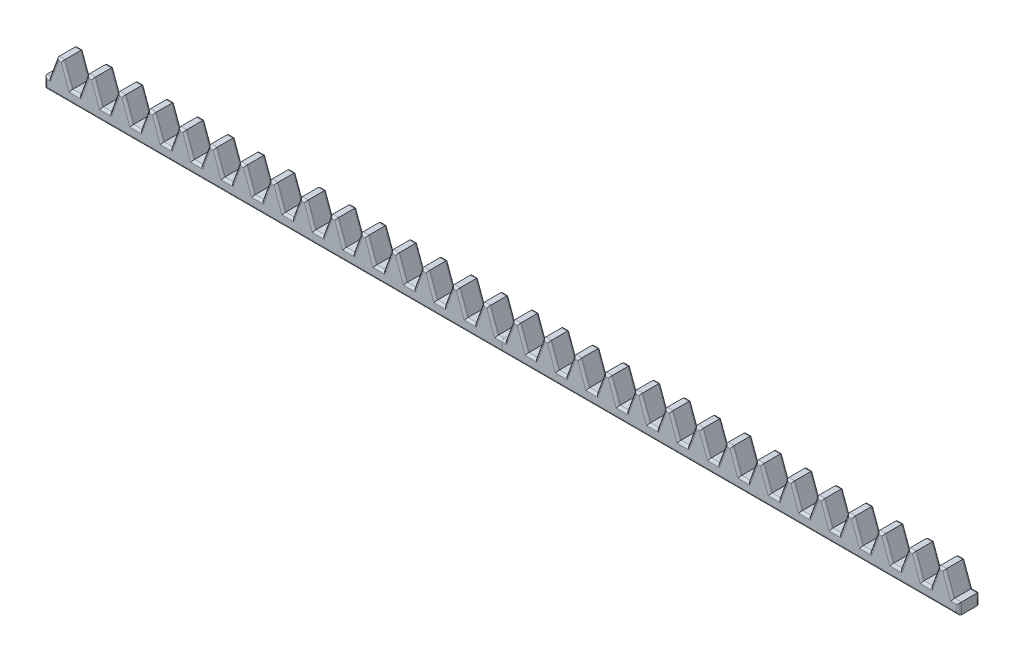
SolidWorks part; units mm, degrees
extrude "Blank" add sketch "BlankSke" against normal blind 8.89
sketch "BlankSke" plane through (0, 0, 0) normal (0, 0, 1) x (1, 0, 0)
  line L1 (0, 0) -> (400.0002, 0)
  line L2 (0, 0) -> (0, 14.3933)
  line L3 (0, 14.3933) -> (400.0002, 14.3933)
  line L4 (400.0002, 0) -> (400.0002, 14.3933)
  dimension "Length" = 400.0002
  dimension "Blank_height" = 14.3933
ref_plane "Plane1" through (0, 0, 0) normal (0, 0, 1) x (1, 0, 0)
ref_plane "Plane2" through (0, 0, 0) normal (0, 1, 0) x (1, 0, 0)
ref_plane "Plane3" through (0, 0, 0) normal (1, 0, 0) x (0, 0, -1)
sketch "HoldingSke" plane through (0, 0, 0) normal (0, 1, 0) x (1, 0, 0)
  line L0 (0, 0) -> (116.7452, -97.9608)
  line L1 (-15, 0) -> (100, 0) construction
  line L2 (0, 0) -> (-2.1039, 2.3779)
  line L3 (0, 0) -> (-11.863, 4.5341)
  line L4 (0, 0) -> (6.5177, 5.6657)
  line L5 (0, 0) -> (-23.7986, -8.8762)
  line L6 (0, 0) -> (-10.5278, -7.1032)
  line L9 (-71.009, 38.7566) -> (417.6302, 216.6067)
  line L10 (-76.2, 71.12) -> (-66.04, 71.12)
  line L11 (0, 0) -> (-8.89, 0)
  line L12 (-76.2, 101.6) -> (-76.0298, 101.6)
  line L13 (24.9733, 27.94) -> (52.9518, 28.4284)
  line L14 (24.9733, 27.94) -> (24.9746, 27.94)
  line L15 (24.9733, 27.94) -> (100.4006, 29.5858)
  circle A0 centre (0, 0) radius 19.05
  circle A1 centre (0, 0) radius 5.08
  circle A2 centre (0, 0) radius 12.7
  dimension "MPH" = 10.16
  dimension "Diameter" = 38.1
  dimension "Num_teeth" = 41
  dimension "Pitch" = 152.4
  dimension "Show_teeth" = 400
  dimension "Thickness" = 12.7
  dimension "Ap" = 20
  dimension "Pitch_height" = 10.16
  dimension "Width" = 8.89
  dimension "Backlash" = 0.1702
  dimension "Addendum_fac" = 1
  dimension "Dedendum_fac" = 1.25
  dimension "Clearance_fac" = 0.25
  dimension "Dedendum_add" = 0.0013
  dimension "Length" = 519.999
sketch "TooCutSkeIll" plane through (0, 0, 0) normal (0, 0, 1) x (1, 0, 0)
  line L0 (-5.3356, 14.2819) -> (-2.1631, 5.5655)
  line L1 (-1.1674, 4.8683) -> (1.1674, 4.8683)
  line L2 (2.1631, 5.5655) -> (5.3356, 14.2819)
  line L3 (400.0002, 14.3933) -> (0, 14.3933) construction
  line L4 (0, 0) -> (0, 64.897) construction
  line L5 (-13.208, 10.16) -> (12.954, 10.16) construction
  line L6 (0, 0) -> (400.0002, 0) construction
  line L7 (3.8354, 10.16) -> (3.8354, 48.7463) construction
  line L8 (-3.8354, 10.16) -> (-3.8354, 48.7463) construction
  line L9 (5.4948, 14.3933) -> (5.4948, 14.4187)
  line L10 (-5.4948, 14.3933) -> (-5.4948, 14.4187)
  line L11 (-5.4948, 14.4187) -> (5.4948, 14.4187)
  arc A0 (1.1674, 4.8683) -> (2.1631, 5.5655) centre (1.1674, 5.9279) ccw
  arc A1 (-2.1631, 5.5655) -> (-1.1674, 4.8683) centre (-1.1674, 5.9279) ccw
  arc A2 (5.4948, 14.3933) -> (5.3356, 14.2819) centre (5.4948, 14.224) ccw
  arc A3 (-5.3356, 14.2819) -> (-5.4948, 14.3933) centre (-5.4948, 14.224) ccw
  dimension "Pitch_height" = 10.16
  dimension "Addendum_plus" = 4.2587
  dimension "Pressure_angle" = 20
  dimension "Gap_width" = 7.6708
  dimension "Dedendum" = 5.2917
extrude "ToothCutIll" [suppressed] cut sketch "TooCutSkeIll" against normal through all
sketch "TooCutSkeSim" plane through (0, 0, 0) normal (0, 0, 1) x (1, 0, 0)
  line L0 (1.9094, 4.8683) -> (-1.9094, 4.8683)
  line L1 (5.3854, 14.4187) -> (1.9094, 4.8683)
  line L2 (0, 17.4625) -> (0, 53.467) construction
  line L3 (5.3854, 14.4187) -> (-5.3854, 14.4187)
  line L6 (-5.3854, 14.4187) -> (-1.9094, 4.8683)
  line L9 (-3.8354, 10.16) -> (3.8354, 10.16) construction
  line L10 (0, 0) -> (400.0002, 0) construction
  line L11 (3.8354, 10.16) -> (3.8354, 53.467) construction
  line L12 (-3.8354, 10.16) -> (-3.8354, 53.467) construction
  dimension "Pitch_height" = 10.16
  dimension "Addendum_plus" = 4.2587
  dimension "Pressure_angle" = 20
  dimension "Gap_width" = 7.6708
  dimension "Dedendum" = 5.2917
extrude "ToothCutSim" cut sketch "TooCutSkeSim" against normal through all
pattern_linear "TeethCuts" count 31 spacing 13.2994 along (1, 0, 0) of "ToothCutIll", "ToothCutSim"
ref_plane "Plane4" through (200.0001, 0, 0) normal (-1, 0, 0) x (0, 0, 1)
fillet "Fillet1" radius 1 74 edges at (395.3395, 9.6308, -8.89) (385.6829, 4.8683, -8.89) (345.7846, 4.8683, -8.89) (332.4852, 4.8683, -8.89) (325.8355, 14.3933, -8.89) (319.1858, 4.8683, -8.89) (305.8864, 4.8683, -8.89) (302.2436, 9.6308, -8.89) (299.2367, 14.3933, -8.89) (296.2298, 9.6308, -8.89) (292.587, 4.8683, -8.89) (265.9882, 4.8683, -8.89) (226.09, 4.8683, -8.89) (219.4402, 14.3933, -8.89) (209.1478, 9.6308, -8.89) (203.1339, 9.6308, -8.89) (200.0001, 0, -8.89) (203.1339, 9.6308, 0) (222.4472, 9.6308, 0) (232.7397, 14.3933, 0) (235.7466, 9.6308, 0) (252.6888, 4.8683, 0) (265.9882, 4.8683, 0) (269.631, 9.6308, 0) (272.6379, 14.3933, 0) (275.6448, 9.6308, 0) (285.9373, 14.3933, 0) (296.2298, 9.6308, 0) (302.2436, 9.6308, 0) (325.8355, 14.3933, 0) (345.7846, 4.8683, 0) (368.7407, 9.6308, 0) (382.0401, 9.6308, 0) (395.3395, 9.6308, 0) (200.0001, 0, 0) (195.8483, 9.6308, -8.89) (172.8923, 4.8683, -8.89) (169.2495, 9.6308, -8.89) (166.2426, 14.3933, -8.89) (163.2357, 9.6308, -8.89) (159.5929, 4.8683, -8.89) (142.6507, 9.6308, -8.89) (113.045, 14.3933, -8.89) (86.4462, 14.3933, -8.89) (66.497, 4.8683, -8.89) (56.8404, 9.6308, -8.89) (53.1976, 4.8683, -8.89) (49.5548, 9.6308, -8.89) (39.8982, 4.8683, -8.89) (33.2485, 14.3933, -8.89) (30.2416, 9.6308, -8.89) (16.9422, 9.6308, -8.89) (0.9547, 4.8683, -8.89) (0, 2.4342, 0) (13.2994, 4.8683, 0) (16.9422, 9.6308, 0) (19.9491, 14.3933, 0) (43.541, 9.6308, 0) (49.5548, 9.6308, 0) (70.1398, 9.6308, 0) (73.1467, 14.3933, 0) (96.7387, 9.6308, 0) (102.7525, 9.6308, 0) (113.045, 14.3933, 0) (119.6947, 4.8683, 0) (136.6369, 9.6308, 0) (139.6438, 14.3933, 0) (149.9363, 9.6308, 0) (152.9432, 14.3933, 0) (166.2426, 14.3933, 0) (176.5351, 9.6308, 0) (189.8345, 9.6308, 0) (192.8414, 14.3933, 0) (195.8483, 9.6308, 0)
split "Split1" trim tools "Plane4" bodies to split 102 resulting bodies 103 104
equation "' \"Pitch@HoldingSke\" = 4"
equation "' \"Num_teeth@HoldingSke\" = 12"
equation "' \"Ap@HoldingSke\" =  20"
equation "' \"Ap@HoldingSke\" = 20"
equation "' \"Width@HoldingSke\" = 0.25"
equation "' \"Show_teeth@HoldingSke\" = 500"
equation "' \"Backlash@HoldingSke\" = 0.009"
equation "' \"Addendum_fac@HoldingSke\" = 1.0"
equation "' \"Dedendum_fac@HoldingSke\" = 1.25"
equation "' \"Dedendum_add@HoldingSke\" = 0.00005"
equation "' \"Clearance_fac@HoldingSke\" = 0.25"
equation "' \"Pitch_height@HoldingSke\" = 1"
equation "' \"Length@HoldingSke\" = 4.71"
equation "\"MPH@HoldingSke\" = \"Dedendum_fac@HoldingSke\" / \"Pitch@HoldingSke\" + 2 * \"Dedendum_add@HoldingSke\" + 0.002"
equation "\"MPH@HoldingSke\" = ((sgn( \"MPH@HoldingSke\" - \"Pitch_height@HoldingSke\")+1)*( \"MPH@HoldingSke\" - \"Pitch_height@HoldingSke\"))/2 + \"Pitch_height@HoldingSke\""
equation "\"Blank_height@BlankSke\" = \"Pitch_height@HoldingSke\" + \"Addendum_fac@HoldingSke\"  / \"Pitch@HoldingSke\" "
equation "\"Length@BlankSke\"=\"Drawer_length@Drawer Assembly Narrow.Assembly\"*0.0393701"
equation "\"Face_width@Blank\" = \"Width@HoldingSke\""
equation "\"Pressure_angle@TooCutSkeIll\" = \"Ap@HoldingSke\""
equation "\"Addendum_plus@TooCutSkeIll\" =  \"Addendum_fac@HoldingSke\"  / \"Pitch@HoldingSke\" + 0.001"
equation "\"Dedendum@TooCutSkeIll\" = \"Dedendum_fac@HoldingSke\"  / \"Pitch@HoldingSke\""
equation "\"Pitch_height@TooCutSkeIll\" =  \"MPH@HoldingSke\""
equation "\"Gap_width@TooCutSkeIll\" = 3.14159265 / 2 / \"Pitch@HoldingSke\" + 6 * \"Backlash@HoldingSke\""
equation "\"Pressure_angle@TooCutSkeSim\" = \"Ap@HoldingSke\""
equation "\"Addendum_plus@TooCutSkeSim\" =  \"Addendum_fac@HoldingSke\"  / \"Pitch@HoldingSke\" + 0.001"
equation "\"Dedendum@TooCutSkeSim\" = \"Dedendum_fac@HoldingSke\"  / \"Pitch@HoldingSke\""
equation "\"Pitch_height@TooCutSkeSim\" =  \"MPH@HoldingSke\""
equation "\"Gap_width@TooCutSkeSim\" = 3.14159265 / 2 / \"Pitch@HoldingSke\" + 6 * \"Backlash@HoldingSke\""
equation "\"Root_fillet@TooCutSkeIll\" = \"Clearance_fac@HoldingSke\" / \"Pitch@HoldingSke\" + \"Dedendum_add@HoldingSke\""
equation "\"Break_rad@TooCutSkeIll\" = 0.02 / \"Pitch@HoldingSke\" * 2"
equation "\"Linear_pitch@TeethCuts\" = 3.14159265 / \"Pitch@HoldingSke\""
equation "\"Num_teeth@HoldingSke\" = int( ( \"Length@HoldingSke\" + 0 ) / (3.14159265 / \"Pitch@HoldingSke\")) + 0.9999  + 1"
equation " \"Num_teeth@TeethCuts\" = int( \"Show_teeth@HoldingSke\" ) + 1"
equation " \"Num_teeth@TeethCuts\" = ((sgn( \"Num_teeth@TeethCuts\" - \"Num_teeth@HoldingSke\" )-1)*( \"Num_teeth@TeethCuts\" - \"Num_teeth@HoldingSke\" ))/-2+ \"Num_teeth@HoldingSke\""
equation " \"Num_teeth@TeethCuts\" = ((sgn( \"Num_teeth@TeethCuts\" - 2.0)+1)*( \"Num_teeth@TeethCuts\" - 2.0))/2 +2.0"
